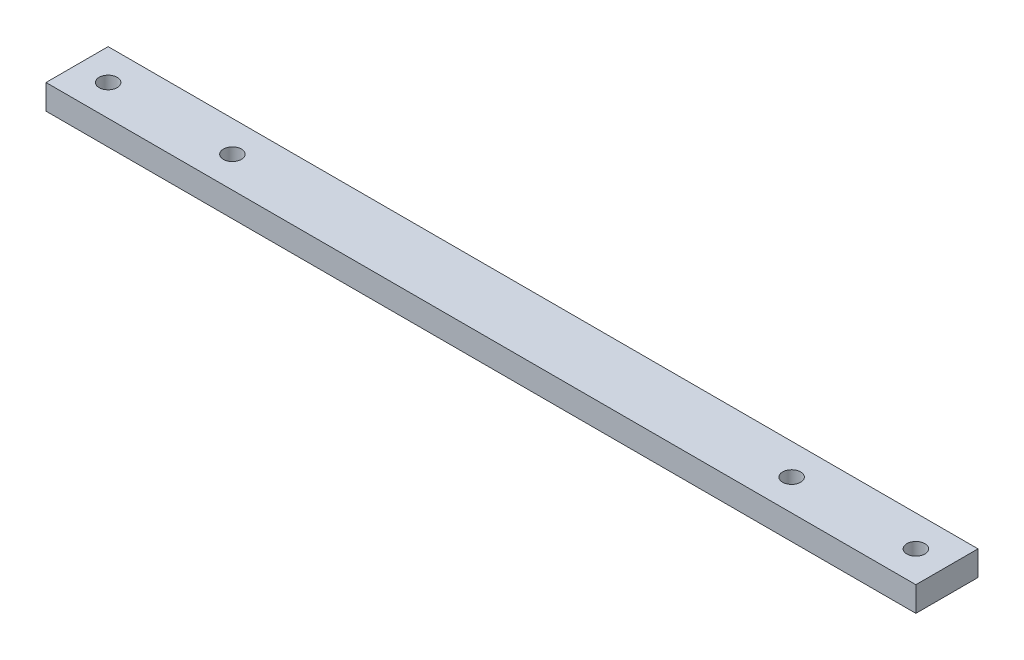
SolidWorks part; units mm, degrees
material "1060-H12"
ref_plane "Front Plane" through (0, 0, 0) normal (0, 0, 1) x (1, 0, 0)
ref_plane "Top Plane" through (0, 0, 0) normal (0, 1, 0) x (1, 0, 0)
ref_plane "Right Plane" through (0, 0, 0) normal (1, 0, 0) x (0, 0, -1)
sketch "Sketch1" plane through (0, 0, 0) normal (0, 1, 0) x (1, 0, 0)
  line L1 (-70, 5) -> (70, 5)
  line L2 (-70, 5) -> (-70, -5)
  line L3 (-70, -5) -> (70, -5)
  line L4 (70, 5) -> (70, -5)
  line L5 (-70, 5) -> (70, -5) construction
  line L6 (-70, -5) -> (70, 5) construction
  point P0 (0, 0)
  dimension "D1" = 140
  dimension "D2" = 10
extrude "Boss-Extrude1" add sketch "Sketch1" along normal blind 4
hole_wizard "M2.5 Clearance Hole1" positions "Sketch2" profile "Sketch3" hole size "M2.5" standard "ISO" end condition through all
sketch "Sketch2" plane through (0, 4, 0) normal (0, 1, 0) x (1, 0, 0)
  line L0 (-70, 5) -> (-70, -5) construction
  line L1 (70, -5) -> (70, 5) construction
  point P0 (-65, 0)
  point P2 (65, 0)
  point P9 (-45, 0)
  point P11 (45, 0)
  dimension "D1" = 5
  dimension "D2" = 5
  dimension "D3" = 20
  dimension "D4" = 20
sketch "Sketch3" plane through (-65, 4, 0) normal (1, 0, 0) x (0, 0, 1)
  line L0 (0, 0) -> (0, 4)
  line L1 (0, 4) -> (1.45, 4)
  line L2 (1.45, 4) -> (1.45, 0)
  line L5 (1.45, 0) -> (0, 0)
  line L11 (0, -6.35) -> (0, 107.95) construction
  dimension "Thru Hole Dia." = 2.9
  dimension "Thru Hole Depth" = 4
